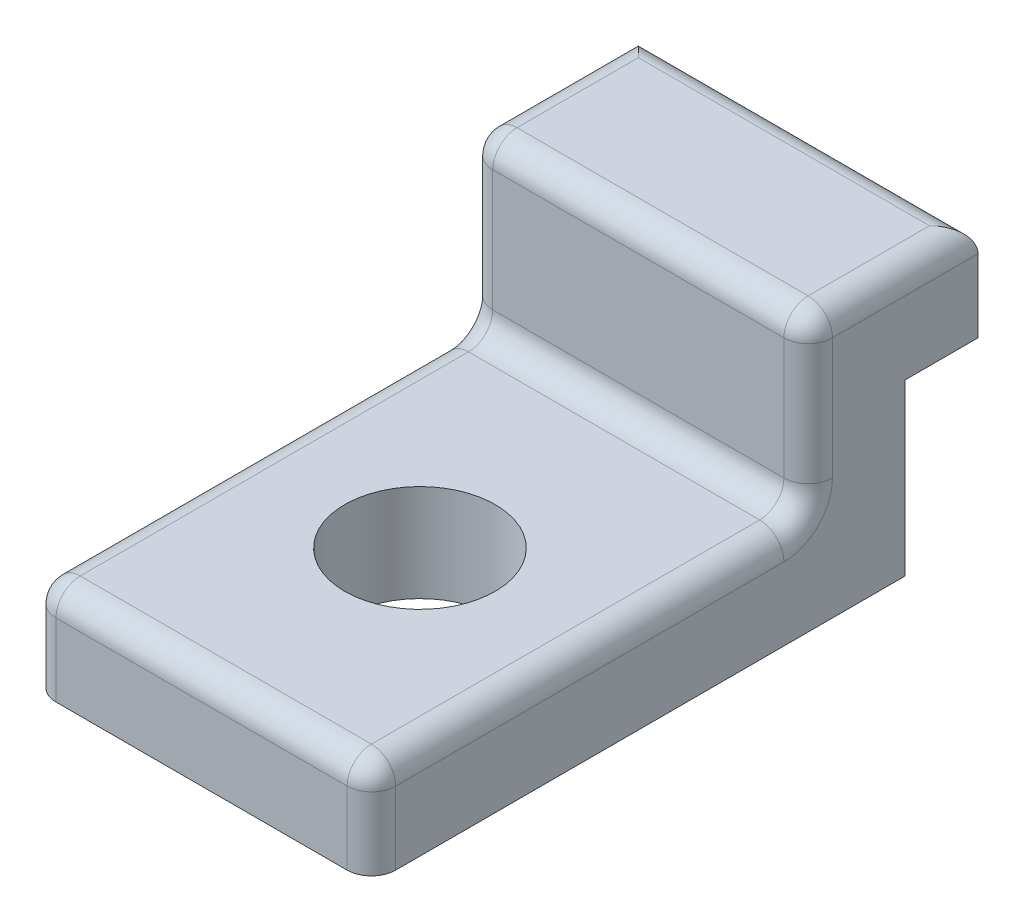
SolidWorks part; units mm, degrees
ref_plane "Plano frontal" through (0, 0, 0) normal (0, 0, 1) x (1, 0, 0)
ref_plane "Plano superior" through (0, 0, 0) normal (0, 1, 0) x (1, 0, 0)
ref_plane "Plano direito" through (0, 0, 0) normal (1, 0, 0) x (0, 0, -1)
sketch "Esboço1" plane through (0, 0, 0) normal (0, 1, 0) x (1, 0, 0)
  line L1 (-3.5, 5.5) -> (3.5, 5.5)
  line L2 (-3.5, 5.5) -> (-3.5, -5.5)
  line L3 (-3.5, -5.5) -> (3.5, -5.5)
  line L4 (3.5, 5.5) -> (3.5, -5.5)
  line L5 (-3.5, 5.5) -> (3.5, -5.5) construction
  line L6 (-3.5, -5.5) -> (3.5, 5.5) construction
  point P0 (0, 0)
  dimension "D1" = 7
  dimension "D2" = 11
extrude "Ressalto-extrusão1" add sketch "Esboço1" along normal blind 2
sketch "Esboço2" plane through (0, 2, 0) normal (0, 1, 0) x (1, 0, 0)
  line L0 (3.5, -5.5) -> (3.5, 5.5) construction
  line L1 (-3.5, 5.5) -> (3.5, 5.5)
  line L2 (-3.5, 5.5) -> (-3.5, 3.5)
  line L3 (-3.5, 3.5) -> (3.5, 3.5)
  line L4 (3.5, 5.5) -> (3.5, 3.5)
  line L5 (-3.5, 5.5) -> (3.5, 3.5) construction
  line L6 (-3.5, 3.5) -> (3.5, 5.5) construction
  point P4 (0, 4.5)
  dimension "D1" = 2
extrude "Ressalto-extrusão2" add sketch "Esboço2" along normal blind 3.5
sketch "Esboço3" plane through (0, 0, -5.5) normal (0, 0, -1) x (-1, 0, 0)
  line L0 (3.5, 5.5) -> (3.5, 0) construction
  line L1 (-3.5, 5.5) -> (3.5, 5.5)
  line L2 (-3.5, 5.5) -> (-3.5, 3.5)
  line L3 (-3.5, 3.5) -> (3.5, 3.5)
  line L4 (3.5, 5.5) -> (3.5, 3.5)
  line L5 (-3.5, 5.5) -> (3.5, 3.5) construction
  line L6 (-3.5, 3.5) -> (3.5, 5.5) construction
  point P4 (0, 4.5)
  dimension "D1" = 2
extrude "Ressalto-extrusão3" add sketch "Esboço3" along normal blind 1.5
sketch "Esboço4" plane through (0, 2, 0) normal (0, 1, 0) x (1, 0, 0)
  line L0 (-3.5, 3.5) -> (3.5, -5.5) construction
  line L1 (3.5, 3.5) -> (-3.5, -5.5) construction
  circle A0 centre (0, -1) radius 1.55
  dimension "D1" = 3.1
extrude "Corte-extrusão1" cut sketch "Esboço4" against normal blind 2
fillet "Filete1" radius 0.5 12 edges at (-3.5, 3.75, -3.5) (3.5, 3.75, -3.5) (3.5, 1, 5.5) (-3.5, 1, 5.5) (0, 5.5, -7) (3.5, 5.5, -5.25) (-3.5, 5.5, -5.25) (0, 2, -3.5) (0, 5.5, -3.5) (-3.5, 2, 1) (3.5, 2, 1) (0, 2, 5.5)
